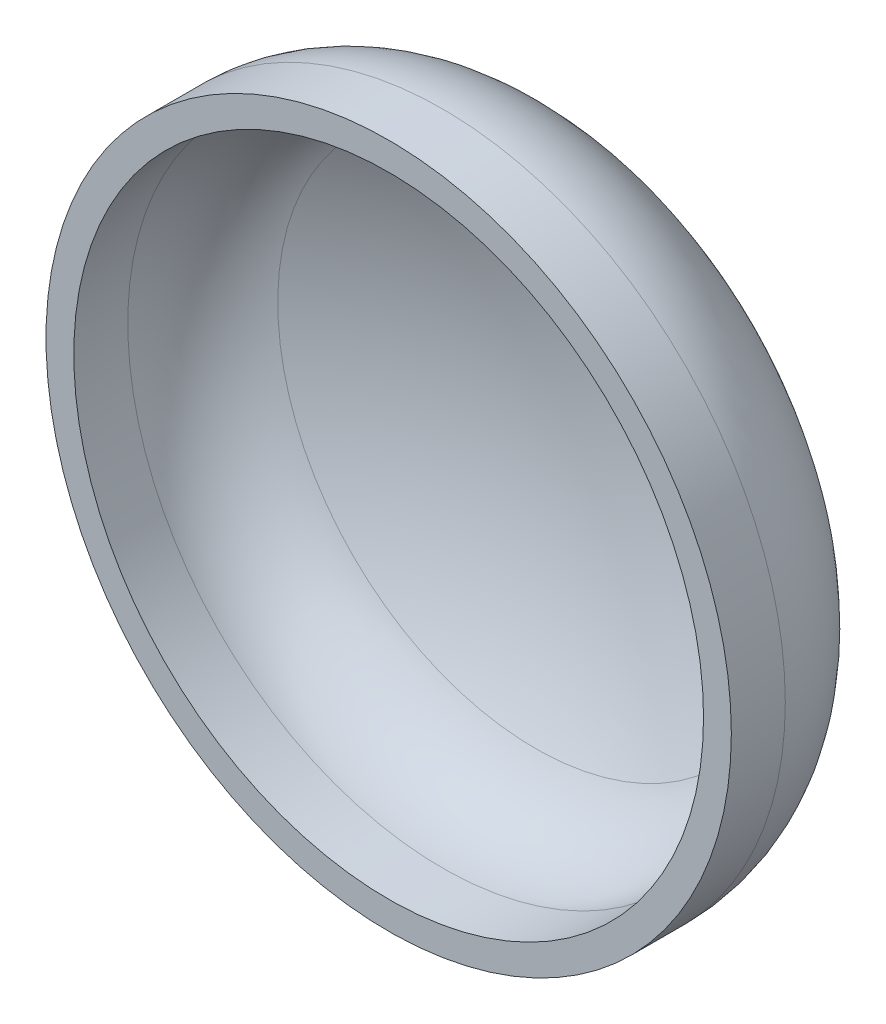
SolidWorks part; units mm, degrees
ref_plane "Front Plane" through (0, 0, 0) normal (0, 0, 1) x (1, 0, 0)
ref_plane "Top Plane" through (0, 0, 0) normal (0, 1, 0) x (1, 0, 0)
ref_plane "Right Plane" through (0, 0, 0) normal (1, 0, 0) x (0, 0, -1)
sketch "Sketch1" plane through (0, 0, 0) normal (1, 0, 0) x (0, 0, -1)
  line L0 (0, 0) -> (222.2643, 0) construction
  line L1 (0, 254) -> (40, 254)
  line L2 (0, 233.4) -> (40, 233.4)
  line L3 (0, 254) -> (0, 233.4)
  line L4 (154.1254, 0) -> (174.7254, 0)
  arc A0 (40, 254) -> (127.1878, 200.2639) centre (40, 156.4) cw
  arc A1 (127.1878, 200.2639) -> (174.7254, 0) centre (-270.8746, 0) cw
  arc A2 (40, 233.4) -> (108.7855, 191.0057) centre (40, 156.4) cw
  arc A3 (108.7855, 191.0057) -> (154.1254, 0) centre (-270.8746, 0) cw
  arc A4 (108.7855, 191.0057) -> (154.1254, 0) centre (-270.8746, 0) cw construction
  point P9 (222.2643, 0)
  dimension "D2" = 77
  dimension "D3" = 20.6
  dimension "D5" = 425
  dimension "D1" = 40
  dimension "D4" = 508
revolve "Revolve1" add sketch "Sketch1" angle 360 about L0
